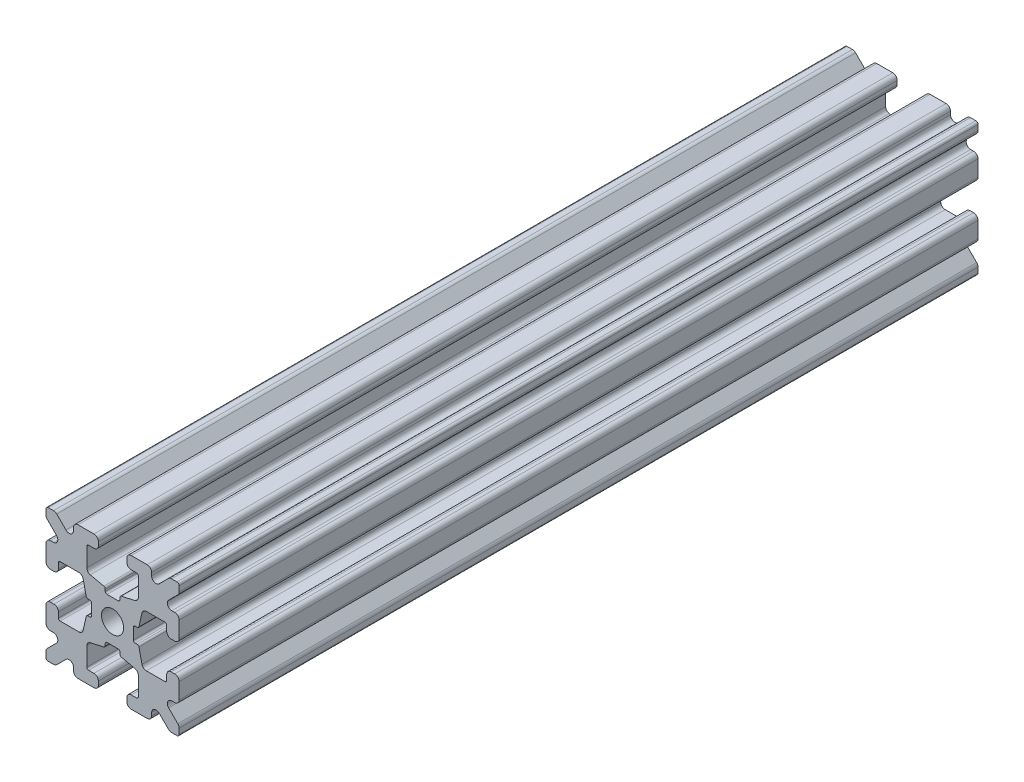
SolidWorks part; units mm, degrees
ref_plane "Front Plane" through (0, 0, 0) normal (0, 0, 1) x (1, 0, 0)
ref_plane "Top Plane" through (0, 0, 0) normal (0, 1, 0) x (1, 0, 0)
ref_plane "Right Plane" through (0, 0, 0) normal (1, 0, 0) x (0, 0, -1)
sketch "Sketch1" plane through (0, 0, 0) normal (0, 0, 1) x (1, 0, 0)
  line L1 (-7.5, -7.5) -> (7.5, -7.5)
  line L2 (-7.5, -7.5) -> (-7.5, 7.5)
  line L3 (-7.5, 7.5) -> (7.5, 7.5)
  line L4 (7.5, -7.5) -> (7.5, 7.5)
  line L5 (-7.5, -7.5) -> (7.5, 7.5) construction
  line L6 (-7.5, 7.5) -> (7.5, -7.5) construction
  circle A0 centre (0, 0) radius 1.25
  point P0 (0, 0)
  dimension "D2" = 2.5
  dimension "D1" = 15
extrude "Boss-Extrude1" add sketch "Sketch1" along normal mid plane 90
fillet "Fillet1" radius 0.25 4 edges at (7.5, -7.5, 0) (-7.5, -7.5, 0) (7.5, 7.5, 0) (-7.5, 7.5, 0)
sketch "Sketch2" plane through (0, 0, 45) normal (0, 0, 1) x (1, 0, 0)
  line L0 (-7.5, 7.25) -> (-7.5, -7.25) construction
  line L1 (-7.5, 1.6) -> (-6.1, 1.6)
  line L2 (-7.5, 1.6) -> (-7.5, -1.6)
  line L3 (-7.5, -1.6) -> (-6.1, -1.6)
  line L4 (-6.1, 1.6) -> (-6.1, 2.9)
  line L5 (0, 0) -> (-12.1036, 0) construction
  line L6 (-6.1, -2.9) -> (-3.4, -2.9)
  line L7 (0, 0) -> (-7.25, 7.25) construction
  line L8 (-6.1, 2.9) -> (-3.4, 2.9)
  line L9 (-3.4, -2.9) -> (-3.4, 2.9)
  line L10 (55, 0) -> (-55, 0) construction
  line L11 (-6.1, -2.9) -> (-6.1, -1.6)
  line L12 (2.9, 6.1) -> (1.6, 6.1)
  line L13 (2.9, 3.4) -> (-2.9, 3.4)
  line L14 (-2.9, 6.1) -> (-2.9, 3.4)
  line L15 (2.9, 6.1) -> (2.9, 3.4)
  line L16 (-1.6, 6.1) -> (-2.9, 6.1)
  line L17 (1.6, 7.5) -> (1.6, 6.1)
  line L18 (-1.6, 7.5) -> (1.6, 7.5)
  line L19 (-1.6, 7.5) -> (-1.6, 6.1)
  line L20 (-1.6, -7.5) -> (-1.6, -6.1)
  line L21 (-1.6, -7.5) -> (1.6, -7.5)
  line L22 (1.6, -7.5) -> (1.6, -6.1)
  line L23 (-1.6, -6.1) -> (-2.9, -6.1)
  line L24 (2.9, -6.1) -> (2.9, -3.4)
  line L25 (-2.9, -6.1) -> (-2.9, -3.4)
  line L26 (2.9, -3.4) -> (-2.9, -3.4)
  line L27 (2.9, -6.1) -> (1.6, -6.1)
  line L28 (6.1, -2.9) -> (6.1, -1.6)
  line L29 (3.4, -2.9) -> (3.4, 2.9)
  line L30 (6.1, 2.9) -> (3.4, 2.9)
  line L31 (6.1, -2.9) -> (3.4, -2.9)
  line L32 (6.1, 1.6) -> (6.1, 2.9)
  line L33 (7.5, -1.6) -> (6.1, -1.6)
  line L34 (7.5, 1.6) -> (7.5, -1.6)
  line L35 (7.5, 1.6) -> (6.1, 1.6)
  dimension "D1" = 3.2
  dimension "D2" = 5.8
  dimension "D3" = 1.4
  dimension "D4" = 2.7
extrude "Cut-Extrude1" cut sketch "Sketch2" against normal through all
sketch "Sketch4" plane through (0, 0, 45) normal (0, 0, 1) x (1, 0, 0)
  line L0 (-3.4, 2.9) -> (-2.75, 0)
  line L1 (55, 0) -> (-55, 0) construction
  line L2 (-2.75, 0) -> (-3.4, -2.9)
  line L3 (-3.4, -2.9) -> (-3.4, 2.9) construction
  line L4 (-3.4, 2.9) -> (-3.4, -2.9)
  line L5 (-2.9, 3.4) -> (0, 2.75)
  line L6 (0, 2.75) -> (2.9, 3.4)
  line L7 (2.9, 3.4) -> (-2.9, 3.4)
  line L8 (3.4, 2.9) -> (2.75, 0)
  line L9 (2.75, 0) -> (3.4, -2.9)
  line L10 (3.4, -2.9) -> (3.4, 2.9)
  line L11 (-2.9, -3.4) -> (0, -2.75)
  line L12 (0, -2.75) -> (2.9, -3.4)
  line L13 (2.9, -3.4) -> (-2.9, -3.4)
  circle A2 centre (0, 0) radius 2.75
  circle A3 centre (0, 0) radius 2.75 construction
  dimension "D1" = 1.5
extrude "Cut-Extrude3" cut sketch "Sketch4" against normal through all
fillet "Fillet3" radius 0.5 16 edges at (-6.1, -1.6, 0) (-7.5, -1.6, 0) (-6.1, 1.6, 0) (-7.5, 1.6, 0) (-1.6, -7.5, 0) (-1.6, -6.1, 0) (1.6, -7.5, 0) (1.6, -6.1, 0) (6.1, -1.6, 0) (7.5, -1.6, 0) (7.5, 1.6, 0) (6.1, 1.6, 0) (1.6, 7.5, 0) (1.6, 6.1, 0) (-1.6, 7.5, 0) (-1.6, 6.1, 0)
fillet "Fillet4" radius 0.5 8 edges at (-3.4, 2.9, 0) (-3.4, -2.9, 0) (2.9, -3.4, 0) (-2.9, -3.4, 0) (3.4, -2.9, 0) (3.4, 2.9, 0) (-2.9, 3.4, 0) (2.9, 3.4, 0)
fillet "Fillet5" radius 3 4 edges at (0, -2.75, 0) (2.75, 0, 0) (-2.75, 0, 0) (0, 2.75, 0)
fillet "Fillet6" radius 0.2 8 edges at (-2.9, -6.1, 0) (2.9, -6.1, 0) (6.1, -2.9, 0) (6.1, 2.9, 0) (2.9, 6.1, 0) (-2.9, 6.1, 0) (-6.1, -2.9, 0) (-6.1, 2.9, 0)
sketch "Sketch5" plane through (0, 0, 45) normal (0, 0, 1) x (1, 0, 0)
  line L0 (0, 0) -> (-7.25, 7.25) construction
  line L1 (-7.5, 6.4393) -> (-5.4607, 4.4)
  line L2 (-6.4393, 7.5) -> (-4.4, 5.4607)
  line L3 (-7.5, 4.4) -> (-5.4607, 4.4)
  line L4 (-3.8003, 2.9) -> (-5.9, 2.9) construction
  line L5 (0, 0) -> (-12.1819, 0) construction
  line L6 (-4.4, 7.5) -> (-4.4, 5.4607)
  line L7 (-2.9, 5.9) -> (-2.9, 3.8003) construction
  line L8 (-7.5, 6.4393) -> (-7.5, 4.4)
  line L9 (-7.5, 7.25) -> (-7.5, 2.1) construction
  line L10 (2.1, -7.5) -> (7.25, -7.5) construction
  line L11 (7.5, -7.25) -> (7.5, -2.1) construction
  line L12 (7.25, 7.5) -> (2.1, 7.5) construction
  line L13 (-2.1, 7.5) -> (-7.25, 7.5) construction
  line L14 (-4.4, 7.5) -> (-6.4393, 7.5)
  line L16 (55, 0) -> (-55, 0) construction
  line L17 (0, 0) -> (0, 10.993) construction
  line L18 (0, -54.6431) -> (0, 54.6431) construction
  line L20 (4.4, 7.5) -> (6.4393, 7.5)
  line L22 (7.5, 6.4393) -> (7.5, 4.4)
  line L23 (4.4, 7.5) -> (4.4, 5.4607)
  line L24 (7.5, 4.4) -> (5.4607, 4.4)
  line L25 (6.4393, 7.5) -> (4.4, 5.4607)
  line L26 (7.5, 6.4393) -> (5.4607, 4.4)
  line L27 (7.5, -6.4393) -> (5.4607, -4.4)
  line L28 (6.4393, -7.5) -> (4.4, -5.4607)
  line L29 (7.5, -4.4) -> (5.4607, -4.4)
  line L30 (4.4, -7.5) -> (4.4, -5.4607)
  line L31 (7.5, -6.4393) -> (7.5, -4.4)
  line L33 (4.4, -7.5) -> (6.4393, -7.5)
  line L36 (-4.4, -7.5) -> (-6.4393, -7.5)
  line L38 (-7.5, -6.4393) -> (-7.5, -4.4)
  line L39 (-4.4, -7.5) -> (-4.4, -5.4607)
  line L40 (-7.5, -4.4) -> (-5.4607, -4.4)
  line L41 (-6.4393, -7.5) -> (-4.4, -5.4607)
  line L42 (-7.5, -6.4393) -> (-5.4607, -4.4)
  dimension "D1" = 1.5
  dimension "D2" = 1.5
  dimension "D3" = 1.5
extrude "Cut-Extrude4" cut sketch "Sketch5" against normal through all
fillet "Fillet8" radius 0.5 24 edges at (-5.4607, 4.4, 0) (-7.5, 4.4, 0) (-5.4607, -4.4, 0) (-7.5, -4.4, 0) (-4.4, -7.5, 0) (-4.4, -5.4607, 0) (4.4, -7.5, 0) (4.4, -5.4607, 0) (5.4607, -4.4, 0) (7.5, -4.4, 0) (7.5, 4.4, 0) (5.4607, 4.4, 0) (4.4, 5.4607, 0) (4.4, 7.5, 0) (-4.4, 5.4607, 0) (-4.4, 7.5, 0) (-6.4393, 7.5, 0) (-7.5, 6.4393, 0) (6.4393, 7.5, 0) (7.5, 6.4393, 0) (6.4393, -7.5, 0) (7.5, -6.4393, 0) (-6.4393, -7.5, 0) (-7.5, -6.4393, 0)
sketch "Sketch6" plane through (0, 0, 45) normal (0, 0, 1) x (1, 0, 0)
  line L0 (0, 0) -> (0, 11.013) construction
  line L1 (0.6561, 2.8971) -> (2.1235, 2.8971) construction
  line L2 (0, -54.6431) -> (0, 54.6431) construction
  line L3 (0, 0) -> (7.25, 7.25) construction
  line L4 (7.5, 0.8255) -> (7.5, -0.8255)
  line L5 (2.3471, 0.8255) -> (7.5, 0.8255)
  line L6 (0, 0) -> (12.4016, 0) construction
  line L7 (0.8255, -7.5) -> (-0.8255, -7.5)
  line L8 (2.3471, -0.8255) -> (2.3471, 0.8255)
  line L9 (0.8255, -2.3471) -> (0.8255, -7.5)
  line L10 (7.5, -0.8255) -> (2.3471, -0.8255)
  line L11 (-7.5, -0.8255) -> (-2.3471, -0.8255)
  line L12 (-2.3471, -0.8255) -> (-2.3471, 0.8255)
  line L13 (-0.8255, -2.3471) -> (0.8255, -2.3471)
  line L14 (-0.8255, 7.5) -> (-0.8255, 2.3471)
  line L15 (-0.8255, 2.3471) -> (0.8255, 2.3471)
  line L16 (-0.8255, -7.5) -> (-0.8255, -2.3471)
  line L17 (0.8255, 2.3471) -> (0.8255, 7.5)
  line L18 (0.8255, 7.5) -> (-0.8255, 7.5)
  line L19 (3.9, 7.5) -> (2.1, 7.5) construction
  line L20 (-2.3471, 0.8255) -> (-7.5, 0.8255)
  line L21 (-7.5, 0.8255) -> (-7.5, -0.8255)
  point P5 (0, -2.5973)
  point P7 (0, 2.5973)
  dimension "D3" = 0.55
  dimension "D1" = 1.651
extrude "Cut-Extrude5" cut sketch "Sketch6" against normal through all
fillet "Fillet10" radius 0.2 16 edges at (-2.935, 0.8255, 0) (-2.935, -0.8255, 0) (2.935, -0.8255, 0) (2.935, 0.8255, 0) (0.8255, 2.935, 0) (-0.8255, 2.935, 0) (-2.3471, 0.8255, 0) (-2.3471, -0.8255, 0) (0.8255, 2.3471, 0) (-0.8255, 2.3471, 0) (2.3471, 0.8255, 0) (2.3471, -0.8255, 0) (0.8255, -2.935, 0) (0.8255, -2.3471, 0) (-0.8255, -2.3471, 0) (-0.8255, -2.935, 0)
